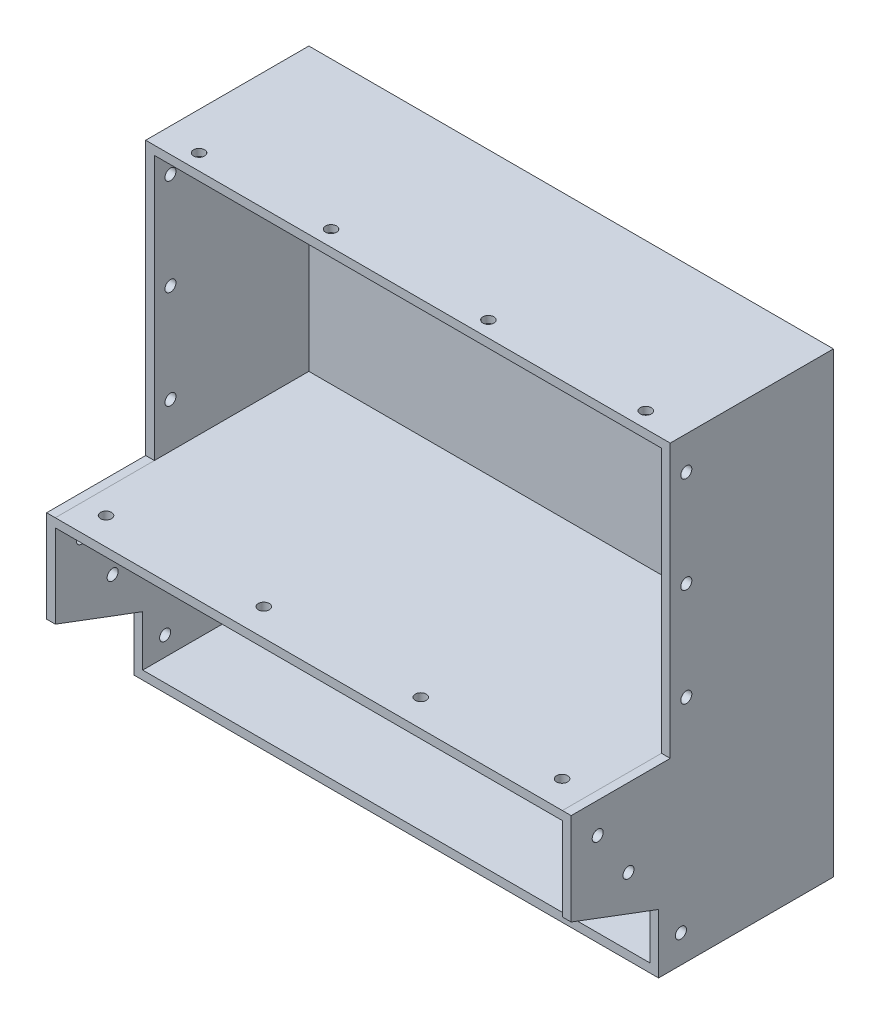
SolidWorks part; units mm, degrees
material "Custom Plastic"
ref_plane "X-Y Datum" through (0, 0, 0) normal (0, 0, 1) x (1, 0, 0)
ref_plane "X-Z Datum" through (0, 0, 0) normal (0, 1, 0) x (1, 0, 0)
ref_plane "Y-Z Datum" through (0, 0, 0) normal (1, 0, 0) x (0, 0, -1)
sketch "Sketch1" plane through (0, 0, 0) normal (0, 0, 1) x (1, 0, 0)
  line L1 (-95.25, -83.058) -> (95.25, -83.058)
  line L2 (-95.25, -83.058) -> (-95.25, 83.058)
  line L3 (-95.25, 83.058) -> (95.25, 83.058)
  line L4 (95.25, -83.058) -> (95.25, 83.058)
  line L5 (-95.25, -83.058) -> (95.25, 83.058) construction
  line L6 (-95.25, 83.058) -> (95.25, -83.058) construction
  point P0 (0, 0)
  dimension "D1" = 166.116
  dimension "D2" = 190.5
extrude "Boss-Extrude1" add sketch "Sketch1" along normal blind 95.25
sketch "Sketch3" plane through (0, 0, 95.25) normal (0, 0, 1) x (1, 0, 0)
  line L0 (-92.075, -49.9618) -> (92.075, -49.9618)
  line L1 (92.075, -61.8913) -> (95.25, -61.8913)
  line L2 (-92.075, -61.8913) -> (92.075, -61.8913)
  line L3 (95.25, -83.058) -> (95.25, 83.058) construction
  line L4 (-92.075, -61.8913) -> (-92.075, -79.883)
  line L5 (-95.25, -49.9618) -> (-95.25, -61.8913)
  line L6 (92.075, -61.8913) -> (92.075, -79.883)
  line L7 (-95.25, 83.058) -> (-95.25, -83.058) construction
  line L8 (-122.0928, 3.2687) -> (-122.1486, 3.2687)
  line L9 (92.075, -79.883) -> (76.2531, -79.883)
  line L13 (-95.25, 32.8917) -> (-92.075, 32.8917)
  line L15 (-122.0786, -16.0951) -> (-122.1486, -16.0951)
  line L17 (95.25, -49.9618) -> (92.075, -49.9618)
  line L18 (-92.075, -79.883) -> (76.2531, -79.883)
  line L21 (-92.075, -49.9618) -> (-95.25, -49.9618)
  line L23 (-81.0858, 79.883) -> (83.8833, 79.883)
  line L25 (-81.0858, 79.883) -> (-92.075, 79.883)
  line L26 (-92.075, 79.883) -> (-92.075, -16.0951)
  line L28 (95.25, 48.6627) -> (92.075, 48.6627)
  line L30 (83.8833, 79.883) -> (92.075, 79.883)
  line L31 (92.075, 79.883) -> (92.075, -16.0951)
  line L33 (-92.075, -16.0951) -> (92.075, -16.0951)
  line L34 (95.25, -49.9618) -> (95.25, -61.8913)
  line L35 (-95.25, -61.8913) -> (-92.075, -61.8913)
extrude "Cut-Extrude1" cut sketch "Sketch3" against normal blind 92.075
sketch "Sketch15" plane through (0, 0, 95.25) normal (0, 0, 1) x (1, 0, 0)
  line L1 (-95.25, 83.058) -> (-95.25, -83.058) construction
  line L3 (95.25, -83.058) -> (95.25, 83.058) construction
  line L4 (95.25, -16.1093) -> (95.25, 83.058)
  line L5 (95.25, 83.058) -> (-95.25, 83.058)
  line L6 (-95.25, 83.058) -> (-95.25, -16.1093)
  line L10 (95.25, -16.1093) -> (92.075, -16.0951)
  line L11 (92.075, -16.0951) -> (92.075, 79.883)
  line L12 (92.075, 79.883) -> (-92.075, 79.883)
  line L13 (-92.075, 79.883) -> (-92.075, -16.0951)
  line L14 (-92.075, -16.0951) -> (92.075, -16.0951) construction
  line L15 (-92.075, 79.883) -> (-92.075, -16.0951) construction
  line L16 (-95.25, -16.1093) -> (-92.075, -16.0951)
extrude "Cut-Extrude5" cut sketch "Sketch15" against normal blind 35.9842
sketch "Sketch17" plane through (0, 0, 95.25) normal (0, 0, 1) x (1, 0, 0)
  line L0 (-95.25, -49.5836) -> (-95.25, -83.058)
  line L2 (-95.25, -83.058) -> (95.25, -83.058)
  line L3 (-95.25, -16.1093) -> (-95.25, -83.058) construction
  line L4 (95.25, -83.058) -> (95.25, -16.1093) construction
  line L5 (95.25, -83.058) -> (95.25, -49.5836)
  line L6 (-95.25, -49.5836) -> (95.25, -49.5836)
extrude "Cut-Extrude6" cut sketch "Sketch17" against normal blind 31.75
sketch "Sketch18" plane through (-95.25, 0, 0) normal (-1, 0, 0) x (0, 0, 1)
  line L0 (63.5, -49.5836) -> (63.5, -61.5061)
  line L1 (63.5, -49.5836) -> (63.5, -83.058) construction
  line L2 (63.5, -61.5061) -> (95.25, -49.5836)
  line L3 (95.25, -49.5836) -> (63.5, -49.5836)
extrude "Boss-Extrude8" add sketch "Sketch18" against normal blind 190.5
sketch "Sketch19" plane through (0, 0, 95.25) normal (0, 0, 1) x (1, 0, 0)
  line L0 (-92.075, -19.2701) -> (-92.075, -49.5836)
  line L2 (95.25, -49.5836) -> (-95.25, -49.5836) construction
  line L4 (92.075, -19.2701) -> (92.075, -49.5836)
  line L6 (92.075, -49.5836) -> (-92.075, -49.5836)
  line L8 (-92.075, -19.2701) -> (92.075, -19.2701)
extrude "Cut-Extrude7" cut sketch "Sketch19" against normal blind 92.075
sketch "Sketch20" plane through (0, -74.8032, 28.0894) normal (0, -0.9362, 0.3515) x (1, 0, 0)
  line L2 (-92.075, -3.8019) -> (-92.075, 82.3961) construction
  line L4 (-92.075, 71.7396) -> (92.075, 71.7396) construction
  line L6 (-92.075, 71.7396) -> (92.075, 71.7396)
  line L12 (92.075, -3.8019) -> (92.075, 82.3961) construction
  line L13 (95.25, 71.7396) -> (92.075, 71.7396) construction
  line L15 (-92.075, 71.7396) -> (-92.075, 37.8249)
  line L16 (95.25, 37.8249) -> (-95.25, 37.8249) construction
  line L17 (92.075, 71.7396) -> (92.075, 37.8249)
  line L18 (92.075, 37.8249) -> (-92.075, 37.8249)
extrude "Cut-Extrude8" cut sketch "Sketch20" against normal blind 13.175
sketch "Sketch21" plane through (0, 0, 63.5) normal (0, 0, 1) x (1, 0, 0)
  line L0 (-92.075, -61.5061) -> (-92.075, -49.5836)
  line L2 (-92.075, -49.5836) -> (92.075, -49.5836)
  line L4 (92.075, -49.5836) -> (92.075, -61.5061)
  line L6 (-92.075, -61.5061) -> (-92.075, -79.883)
  line L7 (-92.075, -79.883) -> (92.075, -79.883)
  line L8 (92.075, -79.883) -> (92.075, -61.5061)
extrude "Cut-Extrude9" cut sketch "Sketch21" against normal blind 60.325
sketch "Sketch23" plane through (0, -83.058, 0) normal (0, -1, 0) x (1, 0, 0)
  circle A4 centre (-83.3197, 53.848) radius 2
  circle A5 centre (-26.4237, 53.848) radius 2
  circle A6 centre (30.4723, 53.848) radius 2
  circle A7 centre (82.2883, 53.848) radius 2
extrude "Cut-Extrude10" cut sketch "Sketch23" against normal blind 2.54
sketch "Sketch24" plane through (0, 83.058, 0) normal (0, 1, 0) x (1, 0, 0)
  line L0 (80.6562, -53.5508) -> (-86.3243, -53.5508) construction
  line L1 (95.25, -59.2658) -> (-95.25, -59.2658) construction
  circle A0 centre (80.6562, -53.5508) radius 2
  circle A3 centre (23.5062, -53.5508) radius 2
  circle A4 centre (-33.6438, -53.5508) radius 2
  circle A7 centre (-81.5688, -53.5508) radius 2
  dimension "D1" = 5.715
extrude "Cut-Extrude11" cut sketch "Sketch24" against normal blind 2.54
sketch "Sketch25" plane through (95.25, 0, 0) normal (1, 0, 0) x (0, 0, -1)
  circle A0 centre (-53.4238, 70.993) radius 2
  circle A1 centre (-53.4238, 35.941) radius 2
  circle A4 centre (-53.4238, 0.889) radius 2 [skipped]
  circle A6 centre (-53.4238, 0.2178) radius 2
  dimension "D2" = 3
extrude "Cut-Extrude12" cut sketch "Sketch25" against normal through all
sketch "Sketch26" plane through (0, -16.0951, 0) normal (0, 1, 0) x (1, 0, 0)
  line L1 (92.075, -59.2658) -> (92.075, -95.25) construction
  line L2 (92.075, -63.7108) -> (-92.075, -63.7108)
  line L3 (-92.075, -59.2658) -> (-92.075, -95.25) construction
  line L5 (-92.075, -79.375) -> (92.075, -79.375)
sketch "Sketch27" plane through (0, -16.0951, 0) normal (0, 1, 0) x (1, 0, 0)
  circle A0 centre (82.042, -85.344) radius 2
  circle A8 centre (30.734, -85.344) radius 2
  circle A11 centre (-26.2686, -85.344) radius 2
  circle A12 centre (-83.566, -85.344) radius 2
extrude "Cut-Extrude13" cut sketch "Sketch27" against normal blind 3.175
sketch "Sketch28" plane through (95.25, 0, 0) normal (1, 0, 0) x (0, 0, -1)
  circle A0 centre (-55.372, -72.898) radius 2
  circle A1 centre (-74.422, -44.3819) radius 2
  circle A2 centre (-85.598, -27.204) radius 2
extrude "Cut-Extrude15" cut sketch "Sketch28" against normal through all
